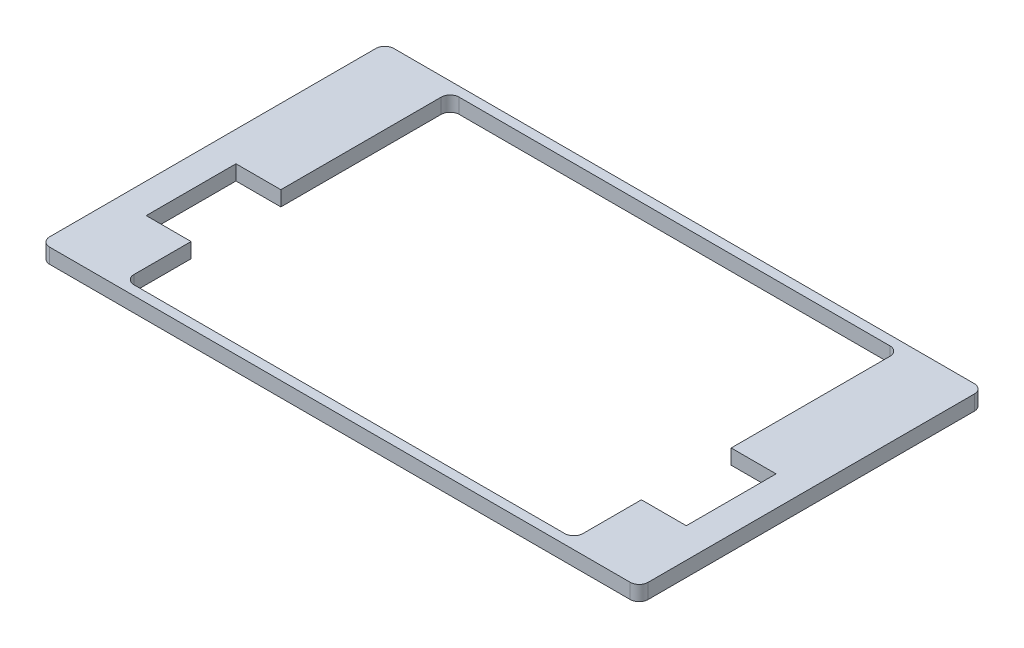
SolidWorks part; units mm, degrees
ref_plane "Front Plane" through (0, 0, 0) normal (0, 0, 1) x (1, 0, 0)
ref_plane "Top Plane" through (0, 0, 0) normal (0, 1, 0) x (1, 0, 0)
ref_plane "Right Plane" through (0, 0, 0) normal (1, 0, 0) x (0, 0, -1)
sketch "Sketch1" plane through (0, 0, 0) normal (0, 1, 0) x (1, 0, 0)
  line L1 (3.81, 0) -> (250.19, 0)
  line L2 (0, 3.81) -> (0, 142.24)
  line L3 (3.81, 146.05) -> (250.19, 146.05)
  line L4 (254, 3.81) -> (254, 142.24)
  line L5 (35.56, 142.025) -> (218.44, 142.025)
  line L6 (31.75, 138.215) -> (31.75, 7.835)
  line L7 (35.56, 4.025) -> (218.44, 4.025)
  line L8 (222.25, 138.215) -> (222.25, 7.835)
  arc A0 (250.19, 0) -> (254, 3.81) centre (250.19, 3.81) ccw
  arc A1 (250.19, 146.05) -> (254, 142.24) centre (250.19, 142.24) cw
  arc A2 (0, 142.24) -> (3.81, 146.05) centre (3.81, 142.24) cw
  arc A3 (3.81, 0) -> (0, 3.81) centre (3.81, 3.81) cw
  arc A4 (31.75, 7.835) -> (35.56, 4.025) centre (35.56, 7.835) ccw
  arc A5 (218.44, 4.025) -> (222.25, 7.835) centre (218.44, 7.835) ccw
  arc A6 (218.44, 142.025) -> (222.25, 138.215) centre (218.44, 138.215) cw
  arc A7 (35.56, 142.025) -> (31.75, 138.215) centre (35.56, 138.215) ccw
  point P11 (254, 0)
  point P14 (254, 146.05)
  point P17 (0, 146.05)
  point P20 (0, 0)
  point P25 (222.25, 4.025)
  point P28 (222.25, 142.025)
  point P31 (31.75, 142.025)
  dimension "D7" = 3.81
  dimension "D1" = 254
  dimension "D2" = 146.05
  dimension "D3" = 138
  dimension "D4" = 190.5
  dimension "D5" = 4.025
  dimension "D6" = 31.75
extrude "Boss-Extrude1" add sketch "Sketch1" along normal blind 6.35
sketch "Sketch2" plane through (0, 6.35, 0) normal (0, 1, 0) x (1, 0, 0)
  line L0 (3.81, 0) -> (250.19, 0) construction
  line L1 (0, 142.24) -> (0, 3.81) construction
  line L2 (254, 3.81) -> (254, 142.24) construction
  circle A0 centre (25.4, 50.8) radius 15.875
  circle A1 centre (228.6, 50.8) radius 15.875
  dimension "D3" = 31.75
  dimension "D4" = 31.75
  dimension "D1" = 50.8
  dimension "D2" = 50.8
  dimension "D5" = 25.4
  dimension "D6" = 25.4
sketch "Sketch3" plane through (0, 0, 0) normal (0, -1, 0) x (1, 0, 0)
  line L1 (222.25, -70.8025) -> (241.3, -70.8025)
  line L2 (222.25, -70.8025) -> (222.25, -32.7025)
  line L3 (222.25, -32.7025) -> (241.3, -32.7025)
  line L4 (241.3, -70.8025) -> (241.3, -32.7025)
  line L6 (215.5825, -35.8775) -> (240.9825, -35.8775) construction
  line L7 (31.75, -138.215) -> (31.75, -7.835) construction
  line L8 (31.75, -70.1675) -> (12.7, -70.1675)
  line L9 (31.75, -70.1675) -> (31.75, -32.0675)
  line L10 (31.75, -32.0675) -> (12.7, -32.0675)
  line L11 (12.7, -70.1675) -> (12.7, -32.0675)
  line L12 (37.7825, -35.2425) -> (12.3825, -35.2425) construction
  dimension "D1" = 19.05
  dimension "D2" = 38.1
  dimension "D3" = 3.175
  dimension "D4" = 19.05
  dimension "D5" = 38.1
  dimension "D6" = 3.175
extrude "Cut-Extrude1" cut sketch "Sketch3" against normal through all
equation "\"D5@Sketch1\"=(\"D2@Sketch1\"-\"D3@Sketch1\")/2"
equation "\"D6@Sketch1\"=(\"D1@Sketch1\"-\"D4@Sketch1\")/2"
